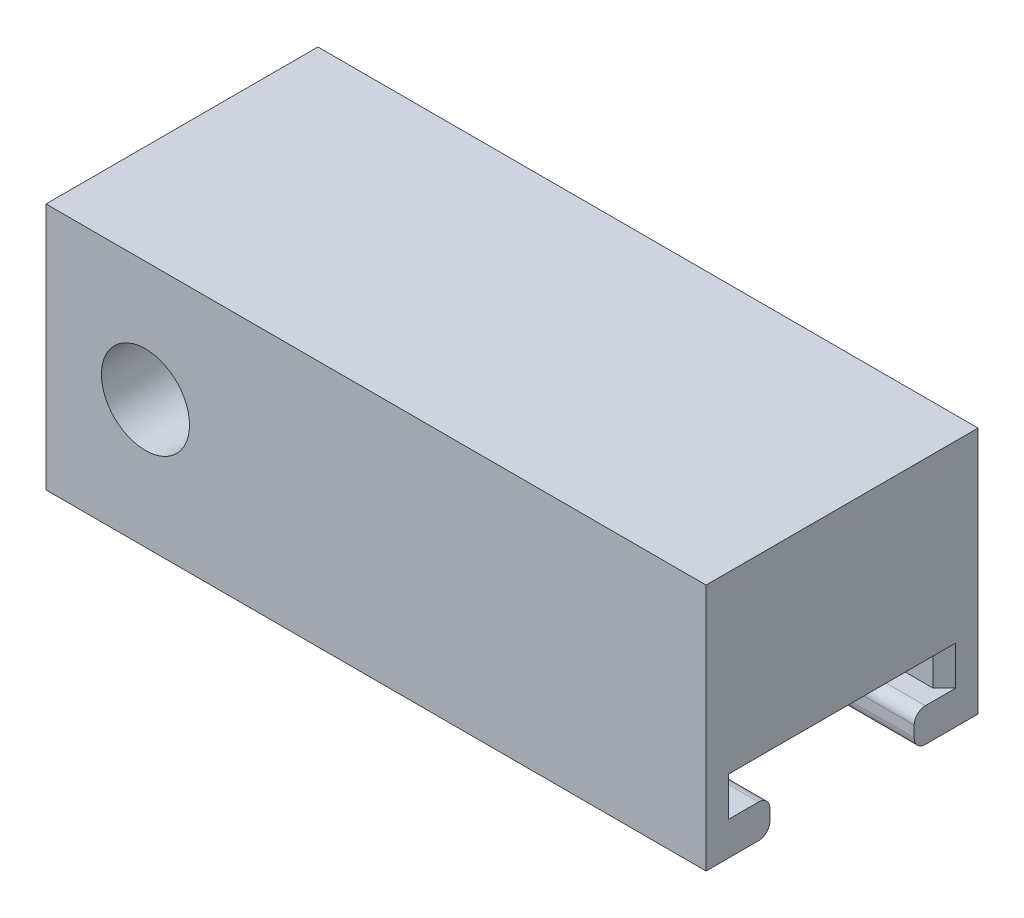
SolidWorks part; units mm, degrees
ref_plane "Front Plane" through (0, 0, 0) normal (0, 0, 1) x (1, 0, 0)
ref_plane "Top Plane" through (0, 0, 0) normal (0, 1, 0) x (1, 0, 0)
ref_plane "Right Plane" through (0, 0, 0) normal (1, 0, 0) x (0, 0, -1)
sketch "Sketch1" plane through (0, 0, 0) normal (1, 0, 0) x (0, 0, -1)
  line L0 (12.1519, 0) -> (12.1481, -9.4374)
  line L1 (12.1481, -9.4374) -> (7.4481, -9.4374)
  line L2 (6.4481, -8.4374) -> (6.4481, -7.4374)
  line L3 (7.4481, -6.4374) -> (10.1481, -6.4374)
  line L4 (10.1481, -6.4374) -> (10.1481, -2.9374)
  line L5 (10.1481, -2.9374) -> (-10.1519, -2.9374)
  line L6 (-10.1519, -2.9374) -> (-10.1519, -6.4374)
  line L7 (-10.1519, -6.4374) -> (-7.4519, -6.4374)
  line L8 (-6.4519, -7.4374) -> (-6.4519, -8.4374)
  line L9 (-12.1519, -9.4374) -> (-12.1519, 0)
  line L10 (-12.1519, 0) -> (12.1519, 0)
  line L11 (-7.4519, -9.4374) -> (-12.1519, -9.4374)
  arc A0 (7.4481, -9.4374) -> (6.4481, -8.4374) centre (7.4481, -8.4374) cw
  arc A1 (6.4481, -7.4374) -> (7.4481, -6.4374) centre (7.4481, -7.4374) cw
  arc A2 (-7.4519, -6.4374) -> (-6.4519, -7.4374) centre (-7.4519, -7.4374) cw
  arc A3 (-6.4519, -8.4374) -> (-7.4519, -9.4374) centre (-7.4519, -8.4374) cw
  point P20 (0, 0)
  dimension "D6" = 1
  dimension "D7" = 1
  dimension "D11" = 1
  dimension "D13" = 4.7
  dimension "D1" = 24.3039
  dimension "D2" = 9.4374
  dimension "D3" = 3.5
  dimension "D4" = 20.3
  dimension "D5" = 2.7
  dimension "D8" = 4.7
  dimension "D9" = 1
  dimension "D10" = 9.4374
  dimension "D12" = 1
  dimension "D14" = 2.7
extrude "Boss-Extrude1" add sketch "Sketch1" along normal blind 59
sketch "Sketch2" plane through (0, 0, 10.1519) normal (0, 0, -1) x (-1, 0, 0)
  line L1 (0, -6.4374) -> (-59, -6.4374)
  line L2 (0, -6.4374) -> (0, -2.9374)
  line L3 (0, -2.9374) -> (-59, -2.9374)
  line L4 (-59, -6.4374) -> (-59, -2.9374)
extrude "Boss-Extrude2" add sketch "Sketch2" along normal blind 1
chamfer "Chamfer1" distance 1 angle 45 1 edges at (59, -4.6874, 9.1519)
mirror "Mirror3" about plane through (0, 0, 0) normal (0, 0, 1) of "Chamfer1", "Boss-Extrude2"
sketch "Sketch3" plane through (9.1519, 0, 0) normal (0, 0, -1) x (-1, 0, 0)
  line L1 (0.6238, -2.9374) -> (-4.3199, -2.9374)
  line L3 (9.1519, -9.4374) -> (9.1519, 0) construction
  arc A0 (-4.3199, -2.9374) -> (0.6238, -2.9374) centre (-1.8481, -0.4656) ccw
  dimension "D2" = 3.4957
  dimension "D1" = 4.9437
  dimension "D3" = 8.5282
extrude "Boss-Extrude3" add sketch "Sketch3" against normal mid plane 6 separate body
sketch "Sketch4" plane through (0, 0, 0) normal (0, 1, 0) x (1, 0, 0)
  line L1 (0, 12.1519) -> (59, 12.1519)
  line L2 (0, 12.1519) -> (0, -12.1519)
  line L3 (0, -12.1519) -> (59, -12.1519)
  line L4 (59, 12.1519) -> (59, -12.1519)
extrude "Boss-Extrude4" add sketch "Sketch4" along normal blind 12.7
sketch "Sketch5" plane through (0, 0, -12.1519) normal (0, 0, -1) x (-1, 0, 0)
  line L0 (-6.8406, 3.5969) -> (-10.9394, 3.5969)
  line L1 (-10.89, 0.4969) -> (-6.89, 0.4969) construction
  line L2 (-10.9394, 0.3969) -> (-6.8406, 0.3969)
  line L3 (-10.89, 0.4969) -> (-6.89, 0.4969)
  line L4 (-59, 0) -> (0, 0)
  line L5 (0, 0) -> (0, 12.7)
  line L6 (0, 12.7) -> (-59, 12.7)
  line L7 (-59, 12.7) -> (-59, 0)
  line L8 (-59, 0) -> (0, 0)
  line L9 (0, 0) -> (0, 12.7)
  line L10 (0, 12.7) -> (-59, 12.7)
  line L11 (-59, 12.7) -> (-59, 0)
  line L12 (-6.89, 3.4969) -> (-10.89, 3.4969) construction
  line L13 (-6.89, 3.4969) -> (-10.89, 3.4969)
  arc A0 (-10.89, 3.4969) -> (-10.89, 0.4969) centre (-8.89, 1.9969) ccw construction
  arc A1 (-6.89, 0.4969) -> (-6.89, 3.4969) centre (-8.89, 1.9969) ccw construction
  arc A2 (-10.89, 3.4969) -> (-10.89, 0.4969) centre (-8.89, 1.9969) ccw
  arc A3 (-6.89, 0.4969) -> (-6.89, 3.4969) centre (-8.89, 1.9969) ccw
  arc A4 (-10.9394, 3.5969) -> (-10.9394, 0.3969) centre (-8.89, 1.9969) ccw
  arc A5 (-6.8406, 0.3969) -> (-6.8406, 3.5969) centre (-8.89, 1.9969) ccw
  dimension "D2" = 0.1
  dimension "D1" = 0
extrude "Cut-Extrude1" cut sketch "Sketch5" against normal blind 6.096 contours L0 A4 L2 A5
sketch "Sketch7" plane through (0, -2.9374, 0) normal (0, -1, 0) x (-1, 0, 0)
  line L0 (0, 0) -> (-59, 0) construction
  line L1 (0, -9.1519) -> (0, 9.1519) construction
  line L2 (-59, -10.1519) -> (-59, 10.1519) construction
ref_plane "Plane1" through (29.5, 0, 0) normal (1, 0, 0) x (0, 0, -1)
sketch "Sketch8" plane through (0, 0, 12.1519) normal (0, 0, 1) x (1, 0, 0)
  circle A0 centre (8.89, 1.9969) radius 3.175 construction
  circle A1 centre (8.89, 1.9969) radius 3.175
  circle A3 centre (8.89, 1.9969) radius 3.937
  dimension "D1" = 0.762
extrude "Cut-Extrude2" cut sketch "Sketch8" against normal blind 11.43 contours A3
sketch "Sketch9" plane through (0, 0, 0) normal (-1, 0, 0) x (0, 0, 1)
  line L0 (-9.1519, -6.4374) -> (-9.1519, -9.4374)
  line L1 (-7.4481, -9.4374) -> (-12.1481, -9.4374) construction
  line L2 (-9.1519, -9.4374) -> (-7.4481, -9.4374)
  line L3 (-7.4481, -6.4374) -> (-9.1519, -6.4374)
  line L4 (0, -12.1756) -> (0, 12.1756) construction
  line L5 (9.1519, -9.4374) -> (7.4481, -9.4374)
  line L6 (9.1519, -6.4374) -> (9.1519, -9.4374)
  line L7 (7.4481, -6.4374) -> (9.1519, -6.4374)
  line L8 (-6.4481, -7.4374) -> (-6.4481, -8.4374)
  line L9 (6.4481, -7.4374) -> (6.4481, -8.4374)
  arc A0 (-7.4481, -9.4374) -> (-6.4481, -8.4374) centre (-7.4481, -8.4374) ccw
  arc A1 (-6.4481, -7.4374) -> (-7.4481, -6.4374) centre (-7.4481, -7.4374) ccw
  arc A2 (6.4481, -7.4374) -> (7.4481, -6.4374) centre (7.4481, -7.4374) cw
  arc A3 (7.4481, -9.4374) -> (6.4481, -8.4374) centre (7.4481, -8.4374) cw
extrude "Cut-Extrude3" cut sketch "Sketch9" against normal blind 25.4
